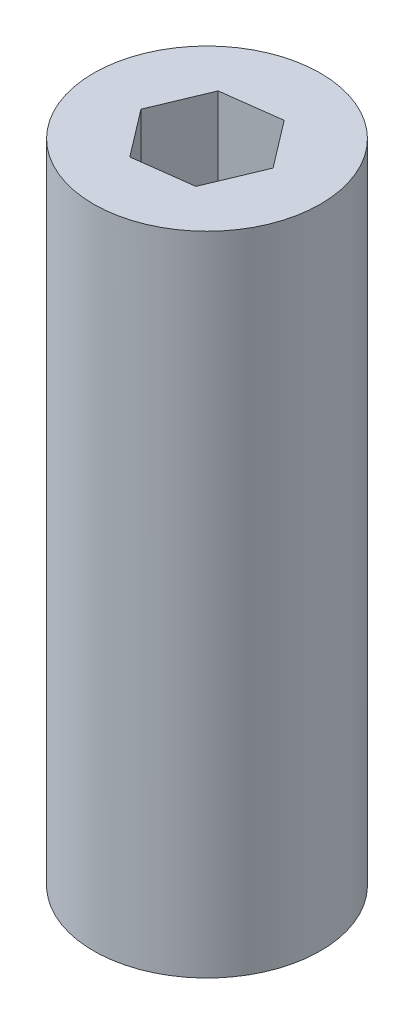
SolidWorks part; units mm, degrees
ref_plane "Front Plane" through (0, 0, 0) normal (0, 0, 1) x (1, 0, 0)
ref_plane "Top Plane" through (0, 0, 0) normal (0, 1, 0) x (1, 0, 0)
ref_plane "Right Plane" through (0, 0, 0) normal (1, 0, 0) x (0, 0, -1)
sketch "Sketch1" plane through (0, 0, 0) normal (0, 1, 0) x (1, 0, 0)
  line L6 (1.5777, -2.0666) -> (2.5786, 0.333)
  line L7 (2.5786, 0.333) -> (1.0009, 2.3996)
  line L8 (1.0009, 2.3996) -> (-1.5777, 2.0666)
  line L9 (-1.5777, 2.0666) -> (-2.5786, -0.333)
  line L10 (-2.5786, -0.333) -> (-1.0009, -2.3996)
  line L11 (-1.0009, -2.3996) -> (1.5777, -2.0666)
  circle A0 centre (0, 0) radius 5
  circle A1 centre (0, 0) radius 2.5 construction
  circle A3 centre (0, 0) radius 2.6 construction
  dimension "D1" = 10
  dimension "D2" = 5.2
extrude "Boss-Extrude1" add sketch "Sketch1" along normal blind 8
sketch "Sketch2" plane through (0, 0, 0) normal (0, -1, 0) x (1, 0, 0)
  circle A0 centre (0, 0) radius 5
  circle A1 centre (0, 0) radius 5 construction
  circle A2 centre (0, 0) radius 2.175
  dimension "D1" = 4.35
extrude "Boss-Extrude2" add sketch "Sketch2" along normal blind 6
sketch "Sketch3" plane through (0, -6, 0) normal (0, -1, 0) x (1, 0, 0)
  circle A0 centre (0, 0) radius 5
  circle A1 centre (0, 0) radius 5 construction
extrude "Boss-Extrude3" add sketch "Sketch3" along normal blind 1.5
sketch "Sketch4" plane through (0, -7.5, 0) normal (0, -1, 0) x (1, 0, 0)
  line L0 (-1.7471, 2.5) -> (1.7471, 2.5)
  circle A0 centre (0, 0) radius 3.05
  circle A1 centre (0, 0) radius 5
  circle A2 centre (0, 0) radius 5 construction
  circle M4 centre (0, 0) radius 5
  dimension "D1" = 6.1
  dimension "D2" = 2.5
extrude "Boss-Extrude4" add sketch "Sketch4" along normal blind 13 contours L0 A0 | A0 M4
